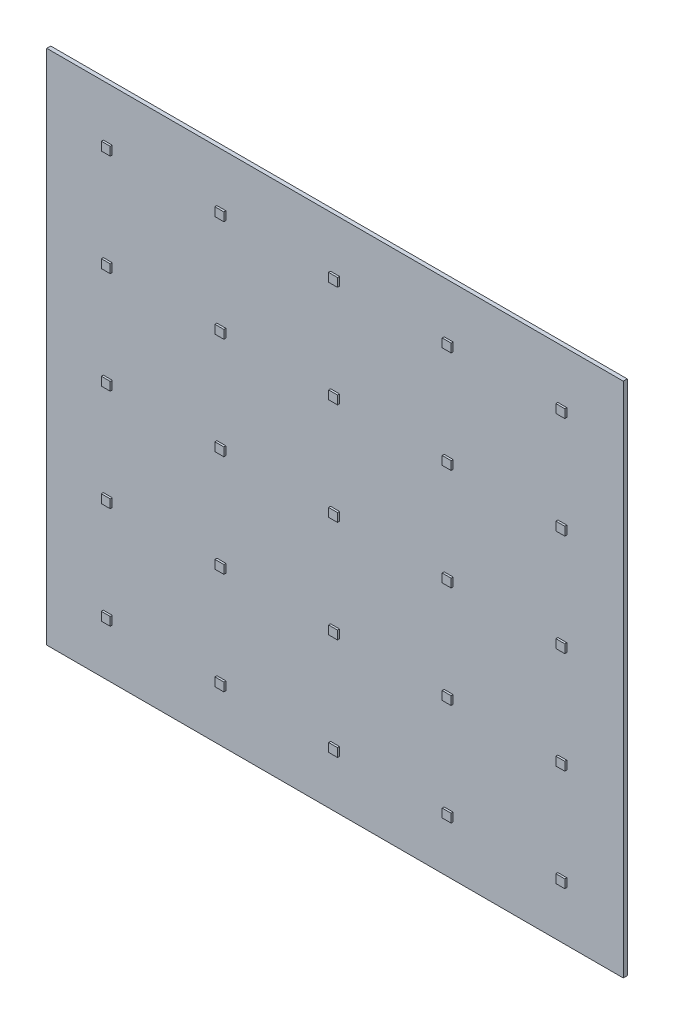
SolidWorks part; units mm, degrees
ref_plane "前视基准面" through (0, 0, 0) normal (0, 0, 1) x (1, 0, 0)
ref_plane "上视基准面" through (0, 0, 0) normal (0, 1, 0) x (1, 0, 0)
ref_plane "右视基准面" through (0, 0, 0) normal (1, 0, 0) x (0, 0, -1)
sketch "草图1" plane through (0, 0, 0) normal (0, 0, 1) x (1, 0, 0)
  line L1 (-72.5, -65) -> (72.5, -65)
  line L2 (-72.5, -65) -> (-72.5, 65)
  line L3 (-72.5, 65) -> (72.5, 65)
  line L4 (72.5, -65) -> (72.5, 65)
  line L5 (-72.5, -65) -> (72.5, 65) construction
  line L6 (-72.5, 65) -> (72.5, -65) construction
  point P0 (0, 0)
  dimension "D1" = 130
  dimension "D2" = 145
extrude "凸台-拉伸1" add sketch "草图1" along normal blind 1
sketch "草图2" plane through (0, 0, 1) normal (0, 0, 1) x (1, 0, 0)
  line L0 (-29.705, 49.9885) -> (-29.705, 52.1385)
  line L1 (-58.285, 49.9885) -> (-56.035, 49.9885)
  line L2 (-58.285, 49.9885) -> (-58.285, 52.1385)
  line L3 (-58.285, 52.1385) -> (-56.035, 52.1385)
  line L4 (-56.035, 49.9885) -> (-56.035, 52.1385)
  line L5 (-58.285, 49.9885) -> (-56.035, 52.1385) construction
  line L6 (-58.285, 52.1385) -> (-56.035, 49.9885) construction
  line L7 (-29.705, 49.9885) -> (-27.455, 49.9885)
  line L8 (-27.455, 49.9885) -> (-27.455, 52.1385)
  line L9 (-29.705, 52.1385) -> (-27.455, 52.1385)
  line L10 (-29.705, 49.9885) -> (-27.455, 52.1385) construction
  line L11 (-29.705, 52.1385) -> (-27.455, 49.9885) construction
  line L12 (-1.125, 49.9885) -> (-1.125, 52.1385)
  line L13 (-1.125, 49.9885) -> (1.125, 49.9885)
  line L14 (1.125, 49.9885) -> (1.125, 52.1385)
  line L15 (-1.125, 52.1385) -> (1.125, 52.1385)
  line L16 (-1.125, 49.9885) -> (1.125, 52.1385) construction
  line L17 (-1.125, 52.1385) -> (1.125, 49.9885) construction
  line L18 (27.455, 49.9885) -> (27.455, 52.1385)
  line L19 (27.455, 49.9885) -> (29.705, 49.9885)
  line L20 (29.705, 49.9885) -> (29.705, 52.1385)
  line L21 (27.455, 52.1385) -> (29.705, 52.1385)
  line L22 (27.455, 49.9885) -> (29.705, 52.1385) construction
  line L23 (27.455, 52.1385) -> (29.705, 49.9885) construction
  line L24 (56.035, 49.9885) -> (56.035, 52.1385)
  line L25 (56.035, 49.9885) -> (58.285, 49.9885)
  line L26 (58.285, 49.9885) -> (58.285, 52.1385)
  line L27 (56.035, 52.1385) -> (58.285, 52.1385)
  line L28 (56.035, 49.9885) -> (58.285, 52.1385) construction
  line L29 (56.035, 52.1385) -> (58.285, 49.9885) construction
  line L30 (-29.705, 24.3885) -> (-29.705, 26.5385)
  line L31 (-29.705, 24.3885) -> (-27.455, 24.3885)
  line L32 (-27.455, 24.3885) -> (-27.455, 26.5385)
  line L33 (-29.705, 26.5385) -> (-27.455, 26.5385)
  line L34 (-29.705, 24.3885) -> (-27.455, 26.5385) construction
  line L35 (-29.705, 26.5385) -> (-27.455, 24.3885) construction
  line L36 (-1.125, 24.3885) -> (-1.125, 26.5385)
  line L37 (-1.125, 24.3885) -> (1.125, 24.3885)
  line L38 (1.125, 24.3885) -> (1.125, 26.5385)
  line L39 (-1.125, 26.5385) -> (1.125, 26.5385)
  line L40 (-1.125, 24.3885) -> (1.125, 26.5385) construction
  line L41 (-1.125, 26.5385) -> (1.125, 24.3885) construction
  line L42 (27.455, 24.3885) -> (27.455, 26.5385)
  line L43 (27.455, 24.3885) -> (29.705, 24.3885)
  line L44 (29.705, 24.3885) -> (29.705, 26.5385)
  line L45 (27.455, 26.5385) -> (29.705, 26.5385)
  line L46 (27.455, 24.3885) -> (29.705, 26.5385) construction
  line L47 (27.455, 26.5385) -> (29.705, 24.3885) construction
  line L48 (56.035, 24.3885) -> (56.035, 26.5385)
  line L49 (56.035, 24.3885) -> (58.285, 24.3885)
  line L50 (58.285, 24.3885) -> (58.285, 26.5385)
  line L51 (56.035, 26.5385) -> (58.285, 26.5385)
  line L52 (56.035, 24.3885) -> (58.285, 26.5385) construction
  line L53 (56.035, 26.5385) -> (58.285, 24.3885) construction
  line L54 (-29.705, -1.2115) -> (-29.705, 0.9385)
  line L55 (-29.705, -1.2115) -> (-27.455, -1.2115)
  line L56 (-27.455, -1.2115) -> (-27.455, 0.9385)
  line L57 (-29.705, 0.9385) -> (-27.455, 0.9385)
  line L58 (-29.705, -1.2115) -> (-27.455, 0.9385) construction
  line L59 (-29.705, 0.9385) -> (-27.455, -1.2115) construction
  line L60 (-1.125, -1.2115) -> (-1.125, 0.9385)
  line L61 (-1.125, -1.2115) -> (1.125, -1.2115)
  line L62 (1.125, -1.2115) -> (1.125, 0.9385)
  line L63 (-1.125, 0.9385) -> (1.125, 0.9385)
  line L64 (-1.125, -1.2115) -> (1.125, 0.9385) construction
  line L65 (-1.125, 0.9385) -> (1.125, -1.2115) construction
  line L66 (27.455, -1.2115) -> (27.455, 0.9385)
  line L67 (27.455, -1.2115) -> (29.705, -1.2115)
  line L68 (29.705, -1.2115) -> (29.705, 0.9385)
  line L69 (27.455, 0.9385) -> (29.705, 0.9385)
  line L70 (27.455, -1.2115) -> (29.705, 0.9385) construction
  line L71 (27.455, 0.9385) -> (29.705, -1.2115) construction
  line L72 (56.035, -1.2115) -> (56.035, 0.9385)
  line L73 (56.035, -1.2115) -> (58.285, -1.2115)
  line L74 (58.285, -1.2115) -> (58.285, 0.9385)
  line L75 (56.035, 0.9385) -> (58.285, 0.9385)
  line L76 (56.035, -1.2115) -> (58.285, 0.9385) construction
  line L77 (56.035, 0.9385) -> (58.285, -1.2115) construction
  line L78 (-29.705, -26.8115) -> (-29.705, -24.6615)
  line L79 (-29.705, -26.8115) -> (-27.455, -26.8115)
  line L80 (-27.455, -26.8115) -> (-27.455, -24.6615)
  line L81 (-29.705, -24.6615) -> (-27.455, -24.6615)
  line L82 (-29.705, -26.8115) -> (-27.455, -24.6615) construction
  line L83 (-29.705, -24.6615) -> (-27.455, -26.8115) construction
  line L84 (-1.125, -26.8115) -> (-1.125, -24.6615)
  line L85 (-1.125, -26.8115) -> (1.125, -26.8115)
  line L86 (1.125, -26.8115) -> (1.125, -24.6615)
  line L87 (-1.125, -24.6615) -> (1.125, -24.6615)
  line L88 (-1.125, -26.8115) -> (1.125, -24.6615) construction
  line L89 (-1.125, -24.6615) -> (1.125, -26.8115) construction
  line L90 (27.455, -26.8115) -> (27.455, -24.6615)
  line L91 (27.455, -26.8115) -> (29.705, -26.8115)
  line L92 (29.705, -26.8115) -> (29.705, -24.6615)
  line L93 (27.455, -24.6615) -> (29.705, -24.6615)
  line L94 (27.455, -26.8115) -> (29.705, -24.6615) construction
  line L95 (27.455, -24.6615) -> (29.705, -26.8115) construction
  line L96 (56.035, -26.8115) -> (56.035, -24.6615)
  line L97 (56.035, -26.8115) -> (58.285, -26.8115)
  line L98 (58.285, -26.8115) -> (58.285, -24.6615)
  line L99 (56.035, -24.6615) -> (58.285, -24.6615)
  line L100 (56.035, -26.8115) -> (58.285, -24.6615) construction
  line L101 (56.035, -24.6615) -> (58.285, -26.8115) construction
  line L102 (-29.705, -52.4115) -> (-29.705, -50.2615)
  line L103 (-29.705, -52.4115) -> (-27.455, -52.4115)
  line L104 (-27.455, -52.4115) -> (-27.455, -50.2615)
  line L105 (-29.705, -50.2615) -> (-27.455, -50.2615)
  line L106 (-29.705, -52.4115) -> (-27.455, -50.2615) construction
  line L107 (-29.705, -50.2615) -> (-27.455, -52.4115) construction
  line L108 (-1.125, -52.4115) -> (-1.125, -50.2615)
  line L109 (-1.125, -52.4115) -> (1.125, -52.4115)
  line L110 (1.125, -52.4115) -> (1.125, -50.2615)
  line L111 (-1.125, -50.2615) -> (1.125, -50.2615)
  line L112 (-1.125, -52.4115) -> (1.125, -50.2615) construction
  line L113 (-1.125, -50.2615) -> (1.125, -52.4115) construction
  line L114 (27.455, -52.4115) -> (27.455, -50.2615)
  line L115 (27.455, -52.4115) -> (29.705, -52.4115)
  line L116 (29.705, -52.4115) -> (29.705, -50.2615)
  line L117 (27.455, -50.2615) -> (29.705, -50.2615)
  line L118 (27.455, -52.4115) -> (29.705, -50.2615) construction
  line L119 (27.455, -50.2615) -> (29.705, -52.4115) construction
  line L120 (56.035, -52.4115) -> (56.035, -50.2615)
  line L121 (56.035, -52.4115) -> (58.285, -52.4115)
  line L122 (58.285, -52.4115) -> (58.285, -50.2615)
  line L123 (56.035, -50.2615) -> (58.285, -50.2615)
  line L124 (56.035, -52.4115) -> (58.285, -50.2615) construction
  line L125 (56.035, -50.2615) -> (58.285, -52.4115) construction
  line L126 (-58.285, 24.3885) -> (-58.285, 26.5385)
  line L127 (-58.285, 24.3885) -> (-56.035, 24.3885)
  line L128 (-56.035, 24.3885) -> (-56.035, 26.5385)
  line L129 (-58.285, 26.5385) -> (-56.035, 26.5385)
  line L130 (-58.285, 24.3885) -> (-56.035, 26.5385) construction
  line L131 (-58.285, 26.5385) -> (-56.035, 24.3885) construction
  line L132 (-58.285, -1.2115) -> (-58.285, 0.9385)
  line L133 (-58.285, -1.2115) -> (-56.035, -1.2115)
  line L134 (-56.035, -1.2115) -> (-56.035, 0.9385)
  line L135 (-58.285, 0.9385) -> (-56.035, 0.9385)
  line L136 (-58.285, -1.2115) -> (-56.035, 0.9385) construction
  line L137 (-58.285, 0.9385) -> (-56.035, -1.2115) construction
  line L138 (-58.285, -26.8115) -> (-58.285, -24.6615)
  line L139 (-58.285, -26.8115) -> (-56.035, -26.8115)
  line L140 (-56.035, -26.8115) -> (-56.035, -24.6615)
  line L141 (-58.285, -24.6615) -> (-56.035, -24.6615)
  line L142 (-58.285, -26.8115) -> (-56.035, -24.6615) construction
  line L143 (-58.285, -24.6615) -> (-56.035, -26.8115) construction
  line L144 (-58.285, -52.4115) -> (-58.285, -50.2615)
  line L145 (-58.285, -52.4115) -> (-56.035, -52.4115)
  line L146 (-56.035, -52.4115) -> (-56.035, -50.2615)
  line L147 (-58.285, -50.2615) -> (-56.035, -50.2615)
  line L148 (-58.285, -52.4115) -> (-56.035, -50.2615) construction
  line L149 (-58.285, -50.2615) -> (-56.035, -52.4115) construction
  line L150 (0, -65) -> (0, 65) construction
  line L151 (-72.5, -65) -> (72.5, -65) construction
  line L152 (72.5, 65) -> (-72.5, 65) construction
  point P0 (-57.16, 51.0635)
  point P8 (-28.58, 51.0635)
  point P13 (0, 51.0635)
  point P18 (28.58, 51.0635)
  point P23 (57.16, 51.0635)
  point P28 (-28.58, 25.4635)
  point P33 (0, 25.4635)
  point P38 (28.58, 25.4635)
  point P43 (57.16, 25.4635)
  point P48 (-28.58, -0.1365)
  point P53 (0, -0.1365)
  point P58 (28.58, -0.1365)
  point P63 (57.16, -0.1365)
  point P68 (-28.58, -25.7365)
  point P73 (0, -25.7365)
  point P78 (28.58, -25.7365)
  point P83 (57.16, -25.7365)
  point P88 (-28.58, -51.3365)
  point P93 (0, -51.3365)
  point P98 (28.58, -51.3365)
  point P103 (57.16, -51.3365)
  point P108 (-57.16, 25.4635)
  point P113 (-57.16, -0.1365)
  point P118 (-57.16, -25.7365)
  point P123 (-57.16, -51.3365)
  dimension "D1" = 2.15
  dimension "D2" = 2.25
  dimension "D3" = 5
  dimension "D4" = 5
extrude "凸台-拉伸2" add sketch "草图2" along normal blind 0.5
